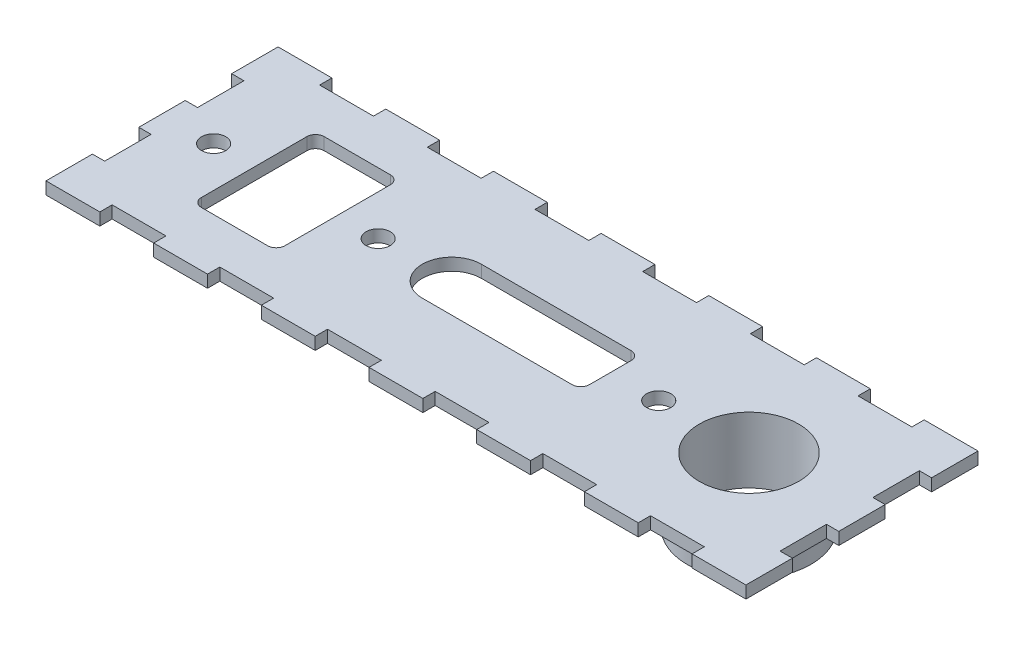
SolidWorks part; units mm, degrees
ref_plane "Front Plane" through (0, 0, 0) normal (0, 0, 1) x (1, 0, 0)
ref_plane "Top Plane" through (0, 0, 0) normal (0, 1, 0) x (1, 0, 0)
ref_plane "Right Plane" through (0, 0, 0) normal (1, 0, 0) x (0, 0, -1)
sketch "Sketch1" plane through (0, 0, 0) normal (0, 1, 0) x (1, 0, 0)
  line L0 (-69.469, 0) -> (75.311, 0) construction
  line L1 (-69.469, 24.003) -> (75.311, 24.003)
  line L2 (-69.469, 24.003) -> (-69.469, -24.003)
  line L3 (-69.469, -24.003) -> (75.311, -24.003)
  line L4 (75.311, 24.003) -> (75.311, -24.003)
  line L5 (23.241, 0) -> (-9.525, 0) construction
  line L7 (-50.419, 12.7) -> (-33.147, 12.7)
  line L8 (-50.419, 12.7) -> (-50.419, -12.7)
  line L9 (-50.419, -12.7) -> (-33.147, -12.7)
  line L10 (-33.147, 12.7) -> (-33.147, -12.7)
  line L11 (-50.419, 12.7) -> (-33.147, -12.7) construction
  line L12 (-50.419, -12.7) -> (-33.147, 12.7) construction
  line L16 (23.241, -6.096) -> (-9.525, -6.096)
  line L17 (23.241, 6.096) -> (23.241, -6.096)
  line L18 (23.241, 6.096) -> (-9.525, 6.096)
  circle A0 centre (51.943, 0) radius 10.287
  arc A2 (-9.525, -6.096) -> (-9.525, 6.096) centre (-9.525, 0) cw
  point P0 (0, 0)
  point P6 (-41.783, 0)
  point P11 (0, 0)
  point P12 (22.479, 0)
  point P30 (-15.621, 0)
  dimension "D9" = 20.574
  dimension "D13" = 6.096
  dimension "D1" = 48.006
  dimension "D2" = 144.78
  dimension "D3" = 19.05
  dimension "D4" = 17.272
  dimension "D5" = 25.4
  dimension "D11" = 12.192
  dimension "D12" = 32.766
  dimension "D14" = 17.526
  dimension "D15" = 28.702
extrude "Boss-Extrude1" add sketch "Sketch1" along normal blind 2.54
fillet "Fillet1" radius 1.778 6 edges at (-33.147, 1.27, 12.7) (-33.147, 1.27, -12.7) (-50.419, 1.27, 12.7) (-50.419, 1.27, -12.7) (23.241, 1.27, 6.096) (23.241, 1.27, -6.096)
sketch "Sketch2" plane through (0, 2.54, 0) normal (0, 1, 0) x (1, 0, 0)
  line L0 (-69.469, 24.003) -> (-69.469, 14.4018)
  line L1 (75.311, 24.003) -> (64.1741, 24.003)
  line L2 (-69.469, 24.003) -> (-69.469, -24.003) construction
  line L3 (-69.469, 24.003) -> (75.311, 24.003) construction
  line L4 (-69.469, 14.4018) -> (-66.929, 14.4018)
  line L5 (-66.929, 14.4018) -> (-66.929, 4.8006)
  line L6 (-66.929, 4.8006) -> (-69.469, 4.8006)
  line L7 (-69.469, 4.8006) -> (-69.469, -4.8006)
  line L8 (-69.469, -4.8006) -> (-66.929, -4.8006)
  line L9 (-66.929, -4.8006) -> (-66.929, -14.4018)
  line L10 (-66.929, -14.4018) -> (-69.469, -14.4018)
  line L11 (-69.469, -14.4018) -> (-69.469, -24.003)
  line L12 (75.311, 24.003) -> (75.311, -24.003) construction
  line L13 (64.1741, 24.003) -> (64.1741, 21.463)
  line L14 (64.1741, 21.463) -> (53.0372, 21.463)
  line L15 (53.0372, 21.463) -> (53.0372, 24.003)
  line L16 (53.0372, 24.003) -> (41.9002, 24.003)
  line L17 (41.9002, 24.003) -> (41.9002, 21.463)
  line L18 (41.9002, 21.463) -> (30.7633, 21.463)
  line L19 (30.7633, 21.463) -> (30.7633, 24.003)
  line L20 (30.7633, 24.003) -> (19.6264, 24.003)
  line L21 (19.6264, 24.003) -> (19.6264, 21.463)
  line L22 (19.6264, 21.463) -> (8.4895, 21.463)
  line L23 (8.4895, 21.463) -> (8.4895, 24.003)
  line L24 (8.4895, 24.003) -> (-2.6475, 24.003)
  line L25 (-2.6475, 24.003) -> (-2.6475, 21.463)
  line L26 (-2.6475, 21.463) -> (-13.7844, 21.463)
  line L27 (-13.7844, 21.463) -> (-13.7844, 24.003)
  line L28 (-13.7844, 24.003) -> (-24.9213, 24.003)
  line L29 (-24.9213, 24.003) -> (-24.9213, 21.463)
  line L30 (-24.9213, 21.463) -> (-36.0582, 21.463)
  line L31 (-36.0582, 21.463) -> (-36.0582, 24.003)
  line L32 (-36.0582, 24.003) -> (-47.1952, 24.003)
  line L33 (-47.1952, 24.003) -> (-47.1952, 21.463)
  line L34 (-47.1952, 21.463) -> (-58.3321, 21.463)
  line L35 (-58.3321, 21.463) -> (-58.3321, 24.003)
  line L36 (-58.3321, 24.003) -> (-69.469, 24.003)
  line L37 (75.311, -24.003) -> (64.1741, -24.003)
  line L38 (64.1741, -24.003) -> (64.1741, -21.463)
  line L39 (64.1741, -21.463) -> (53.0372, -21.463)
  line L40 (53.0372, -21.463) -> (53.0372, -24.003)
  line L41 (53.0372, -24.003) -> (41.9002, -24.003)
  line L42 (41.9002, -24.003) -> (41.9002, -21.463)
  line L43 (41.9002, -21.463) -> (30.7633, -21.463)
  line L44 (30.7633, -21.463) -> (30.7633, -24.003)
  line L45 (30.7633, -24.003) -> (19.6264, -24.003)
  line L46 (19.6264, -24.003) -> (19.6264, -21.463)
  line L47 (19.6264, -21.463) -> (8.4895, -21.463)
  line L48 (8.4895, -21.463) -> (8.4895, -24.003)
  line L49 (8.4895, -24.003) -> (-2.6475, -24.003)
  line L50 (-2.6475, -24.003) -> (-2.6475, -21.463)
  line L51 (-2.6475, -21.463) -> (-13.7844, -21.463)
  line L52 (-13.7844, -21.463) -> (-13.7844, -24.003)
  line L53 (-13.7844, -24.003) -> (-24.9213, -24.003)
  line L54 (-24.9213, -24.003) -> (-24.9213, -21.463)
  line L55 (-24.9213, -21.463) -> (-36.0582, -21.463)
  line L56 (-36.0582, -21.463) -> (-36.0582, -24.003)
  line L57 (-36.0582, -24.003) -> (-47.1952, -24.003)
  line L58 (-47.1952, -24.003) -> (-47.1952, -21.463)
  line L59 (-47.1952, -21.463) -> (-58.3321, -21.463)
  line L60 (-58.3321, -21.463) -> (-58.3321, -24.003)
  line L61 (-58.3321, -24.003) -> (-69.469, -24.003)
  line L63 (-69.469, -24.003) -> (75.311, -24.003) construction
  line L64 (75.311, 24.003) -> (75.311, 14.4018)
  line L65 (75.311, 14.4018) -> (72.771, 14.4018)
  line L66 (72.771, 14.4018) -> (72.771, 4.8006)
  line L67 (72.771, 4.8006) -> (75.311, 4.8006)
  line L68 (75.311, 4.8006) -> (75.311, -4.8006)
  line L69 (75.311, -4.8006) -> (72.771, -4.8006)
  line L70 (72.771, -4.8006) -> (72.771, -14.4018)
  line L71 (72.771, -14.4018) -> (75.311, -14.4018)
  line L72 (75.311, -14.4018) -> (75.311, -24.003)
  dimension "D1" = 2.54
extrude "Cut-Extrude1" cut sketch "Sketch2" against normal blind 2.54 flip side to cut
sketch "Sketch3" plane through (0, 2.54, 0) normal (0, 1, 0) x (1, 0, 0)
  line L0 (-69.469, 0) -> (75.311, 0) construction
  line L1 (-69.469, 4.8006) -> (-69.469, -4.8006) construction
  line L2 (-50.419, 10.922) -> (-50.419, -10.922) construction
  line L3 (75.311, 4.8006) -> (75.311, -4.8006) construction
  line L5 (-16.383, 0) -> (22.479, 0) construction
  line L7 (3.048, 0) -> (3.0375, 0.1223) construction
  line L8 (41.656, 0) -> (62.23, 0) construction
  line L9 (51.943, 0) -> (51.181, 0.1223) construction
  circle A1 centre (51.943, 0) radius 10.287 construction
  circle A2 centre (-58.801, 0) radius 2.5
  circle A5 centre (-24.765, 0) radius 2.5
  circle A6 centre (33.274, 0) radius 2.5
  dimension "D1" = 5
  dimension "D2" = 8.382
  dimension "D3" = 8.382
  dimension "D4" = 8.382
extrude "Cut-Extrude2" cut sketch "Sketch3" against normal through all
sketch "Sketch4" plane through (0, 0, 0) normal (0, -1, 0) x (1, 0, 0)
  line L0 (41.656, 0) -> (39.116, 0) construction
  circle A0 centre (51.943, 0) radius 12.827
  circle A1 centre (51.943, 0) radius 10.287
  circle A2 centre (51.943, 0) radius 10.287 construction
  dimension "D1" = 2.54
extrude "Boss-Extrude2" add sketch "Sketch4" along normal blind 11.049
